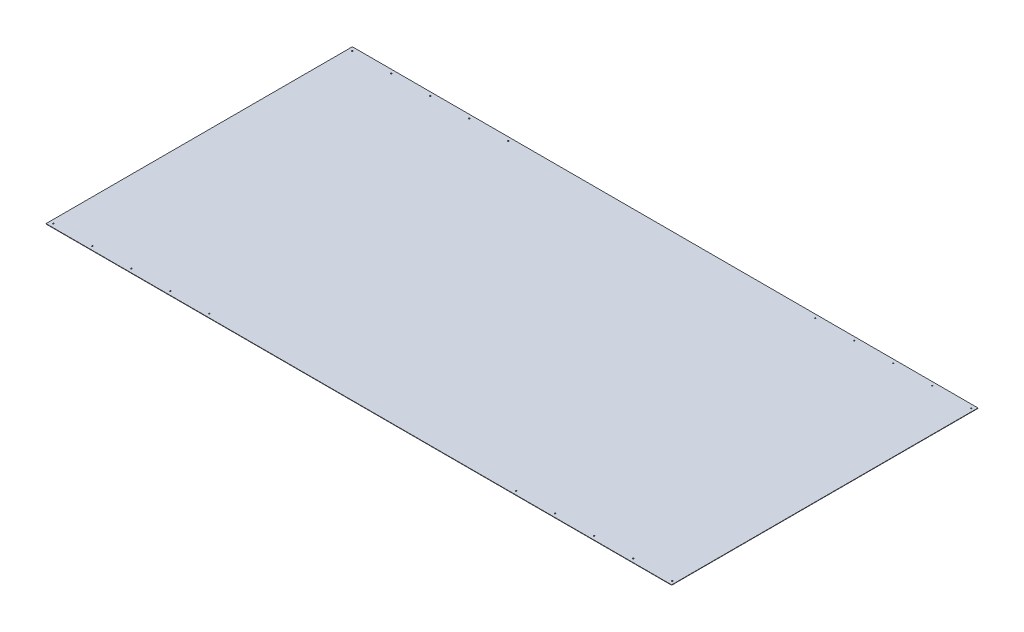
SolidWorks part; units mm, degrees
material "5052-H32"
ref_plane "Front Plane" through (0, 0, 0) normal (0, 0, 1) x (1, 0, 0)
ref_plane "Top Plane" through (0, 0, 0) normal (0, 1, 0) x (1, 0, 0)
ref_plane "Right Plane" through (0, 0, 0) normal (1, 0, 0) x (0, 0, -1)
sketch "Sketch1" plane through (0, 0, 0) normal (0, 1, 0) x (1, 0, 0)
  line L1 (1704.25, -834.5) -> (-1704.25, -834.5)
  line L2 (1704.25, -834.5) -> (1704.25, 834.5)
  line L3 (1704.25, 834.5) -> (-1704.25, 834.5)
  line L4 (-1704.25, -834.5) -> (-1704.25, 834.5)
  line L5 (1704.25, -834.5) -> (-1704.25, 834.5) construction
  line L6 (1704.25, 834.5) -> (-1704.25, -834.5) construction
  point P0 (0, 0)
  dimension "D1" = 1669
  dimension "D2" = 3408.5
extrude "Boss-Extrude1" add sketch "Sketch1" along normal blind 2
sketch "Sketch3" plane through (0, 2, 0) normal (0, 1, 0) x (1, 0, 0)
  line L0 (-1704.25, 834.5) -> (-1704.25, -834.5) construction
  line L1 (1704.25, 834.5) -> (-1704.25, 834.5) construction
  line L2 (-1704.25, -834.5) -> (1704.25, -834.5) construction
  line L3 (1704.25, -834.5) -> (1704.25, 834.5) construction
  circle A0 centre (-1684.25, 814.5) radius 3.25
  circle A1 centre (-1684.25, -814.5) radius 3.25
  circle A2 centre (-1471.75, 814.5) radius 3.25
  circle A3 centre (-1471.75, -814.5) radius 3.25
  circle A4 centre (-1259.25, 814.5) radius 3.25
  circle A5 centre (-1259.25, -814.5) radius 3.25
  circle A6 centre (-1046.75, 814.5) radius 3.25
  circle A7 centre (-1046.75, -814.5) radius 3.25
  circle A8 centre (-834.25, 814.5) radius 3.25
  circle A9 centre (-834.25, -814.5) radius 3.25
  circle A10 centre (1687.25, 814.5) radius 3.25
  circle A11 centre (1687.25, -814.5) radius 3.25
  circle A12 centre (1474.75, 814.5) radius 3.25
  circle A13 centre (1474.75, -814.5) radius 3.25
  circle A14 centre (1262.25, 814.5) radius 3.25
  circle A15 centre (1262.25, -814.5) radius 3.25
  circle A16 centre (1049.75, 814.5) radius 3.25
  circle A17 centre (1049.75, -814.5) radius 3.25
  circle A18 centre (837.25, 814.5) radius 3.25
  circle A19 centre (837.25, -814.5) radius 3.25
  dimension "D2" = 6.5
  dimension "D9" = 6.5
  dimension "D1" = 20
  dimension "D3" = 20
  dimension "D4" = 20
  dimension "D6" = 20
  dimension "D7" = 20
  dimension "D8" = 17
  dimension "D11" = 212.5
  dimension "D12" = 212.5
  dimension "D5" = 5
  dimension "D10" = 5
extrude "Cut-Extrude1" cut sketch "Sketch3" against normal blind 10
